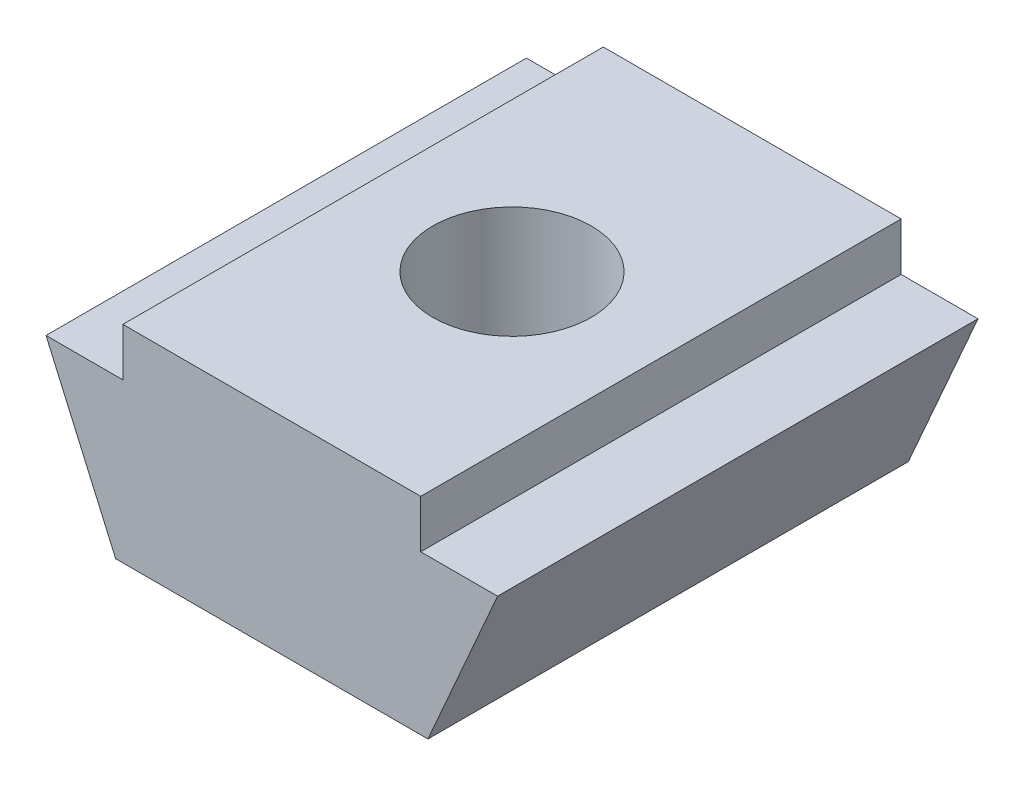
SolidWorks part; units mm, degrees
ref_plane "Front Plane" through (0, 0, 0) normal (0, 0, 1) x (1, 0, 0)
ref_plane "Top Plane" through (0, 0, 0) normal (0, 1, 0) x (1, 0, 0)
ref_plane "Right Plane" through (0, 0, 0) normal (1, 0, 0) x (0, 0, -1)
sketch "Sketch1" plane through (0, 0, 0) normal (0, 0, 1) x (1, 0, 0)
  line L0 (-3.25, 0) -> (3.25, 0)
  line L1 (3.25, 0) -> (4.7, 3.3)
  line L2 (4.7, 3.3) -> (3.1, 3.3)
  line L3 (3.1, 3.3) -> (3.1, 4.3)
  line L4 (3.1, 4.3) -> (-3.1, 4.3)
  line L5 (0, 0) -> (0, 4.3) construction
  line L6 (-3.1, 3.3) -> (-3.1, 4.3)
  line L7 (-4.7, 3.3) -> (-3.1, 3.3)
  line L8 (-3.25, 0) -> (-4.7, 3.3)
  point P4 (0, 0)
  dimension "D1" = 4.3
  dimension "D2" = 6.2
  dimension "D3" = 6.5
  dimension "D4" = 1
  dimension "D5" = 9.4
extrude "Boss-Extrude1" add sketch "Sketch1" along normal mid plane 10
hole_wizard "M4x0.7 Tapped Hole2" positions "Sketch4" profile "Sketch5" tap size "M4x0.7" standard "ANSI Metric"
sketch "Sketch4" plane through (0, 4.3, 0) normal (0, 1, 0) x (1, 0, 0)
  point P0 (0, 0)
sketch "Sketch5" plane through (0, 4.3, 0) normal (1, 0, 0) x (0, 0, 1)
  line L0 (0, 0) -> (0, 12.4914)
  line L1 (0, 12.4914) -> (1.65, 11.5)
  line L2 (1.65, 11.5) -> (1.65, 0)
  line L5 (1.65, 0) -> (0, 0)
  line L10 (0, 12.4914) -> (-1.65, 11.5) construction
  line L11 (0, -6.35) -> (0, 107.95) construction
  dimension "Tap Drill Dia." = 3.3
  dimension "Tap Drill Depth" = 11.5
  dimension "Drill Angle" = 118
